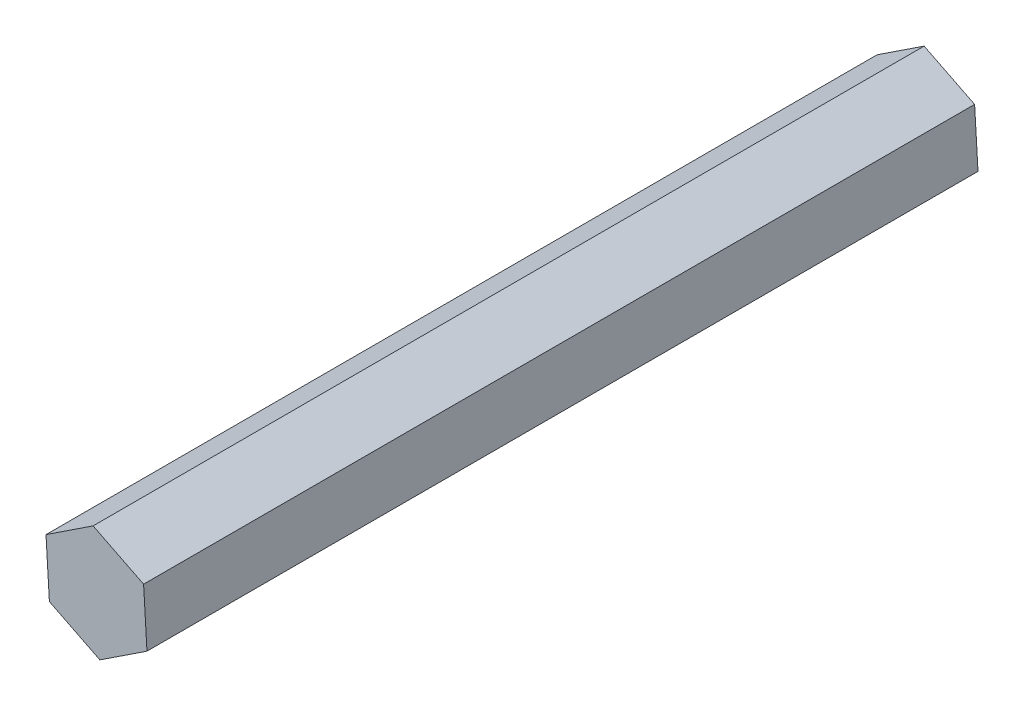
SolidWorks part; units mm, degrees
ref_plane "Front Plane" through (0, 0, 0) normal (0, 0, 1) x (1, 0, 0)
ref_plane "Top Plane" through (0, 0, 0) normal (0, 1, 0) x (1, 0, 0)
ref_plane "Right Plane" through (0, 0, 0) normal (1, 0, 0) x (0, 0, -1)
sketch "Sketch1" plane through (0, 0, 0) normal (0, 0, 1) x (1, 0, 0)
  line L1 (-6.5583, 3.2791) -> (-6.1189, -4.04)
  line L2 (-6.1189, -4.04) -> (0.4393, -7.3192)
  line L3 (0.4393, -7.3192) -> (6.5583, -3.2791)
  line L4 (6.5583, -3.2791) -> (6.1189, 4.04)
  line L5 (6.1189, 4.04) -> (-0.4393, 7.3192)
  line L6 (-0.4393, 7.3192) -> (-6.5583, 3.2791)
  circle A0 centre (0, 0) radius 6.35 construction
  dimension "D1" = 12.7
extrude "Boss-Extrude1" add sketch "Sketch1" along normal blind 107.95 contours L3 L4 L5 L6 L1 L2
